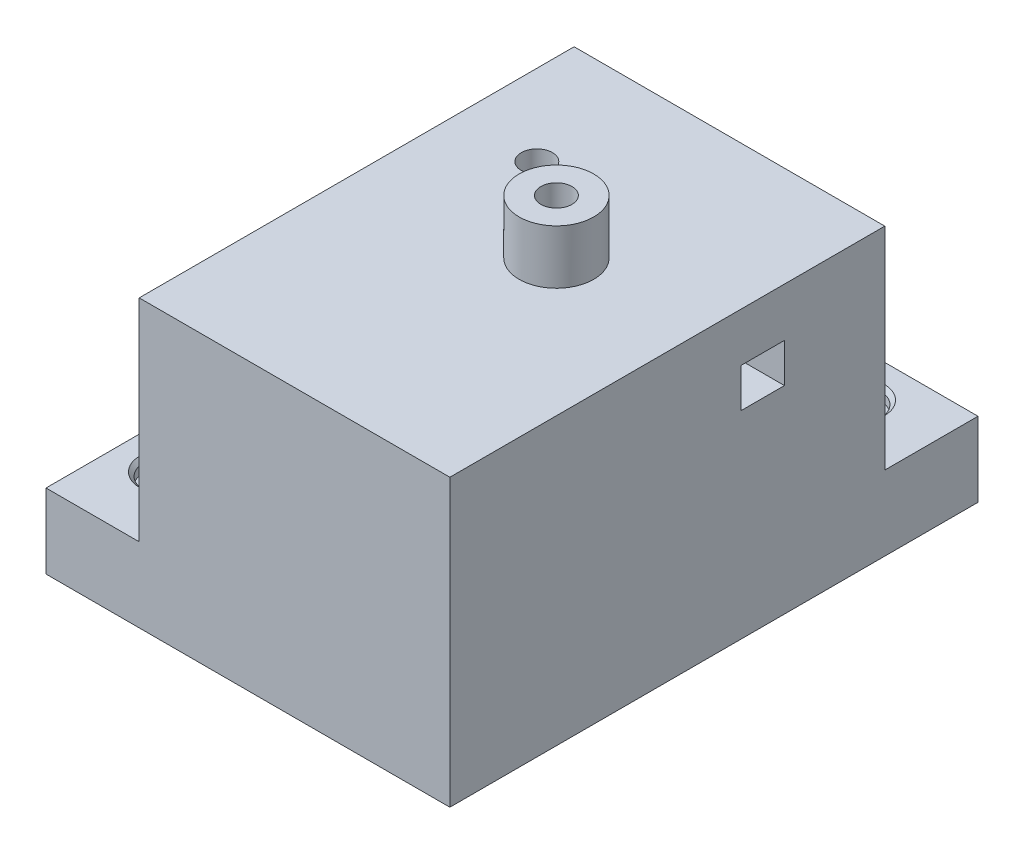
SolidWorks part; units mm, degrees
ref_plane "Front Plane" through (0, 0, 0) normal (0, 0, 1) x (1, 0, 0)
ref_plane "Top Plane" through (0, 0, 0) normal (0, 1, 0) x (1, 0, 0)
ref_plane "Right Plane" through (0, 0, 0) normal (1, 0, 0) x (0, 0, -1)
sketch "Sketch1" plane through (0, 0, 0) normal (0, 1, 0) x (1, 0, 0)
  line L1 (0, -1.9634) -> (-50, -1.9634)
  line L2 (0, -1.9634) -> (0, -71.9634)
  line L3 (0, -71.9634) -> (-50, -71.9634)
  line L4 (-50, -1.9634) -> (-50, -71.9634)
  dimension "D1" = 50
  dimension "D2" = 70
extrude "Boss-Extrude1" add sketch "Sketch1" along normal blind 46
sketch "Sketch2" plane through (0, 0, 71.9634) normal (0, 0, 1) x (1, 0, 0)
  line L0 (-50, 46) -> (0, 46) construction
  line L1 (0, 46) -> (0, 0) construction
  circle A0 centre (-25, 35) radius 3.15
  dimension "D1" = 6.3
  dimension "D2" = 11
  dimension "D3" = 25
extrude "Cut-Extrude1" cut sketch "Sketch2" against normal blind 10
sketch "Sketch3" plane through (0, 0, 0) normal (1, 0, 0) x (0, 0, -1)
  line L2 (-21.9634, 38.15) -> (-25.1134, 38.15)
  line L3 (-25.1134, 38.15) -> (-25.1134, 31.85)
  line L4 (-25.1134, 31.85) -> (-18.1134, 31.85)
  line L5 (-18.1134, 31.85) -> (-18.1134, 38.15)
  line L6 (-18.1134, 38.15) -> (-21.9634, 38.15)
  line L7 (-1.9634, 46) -> (-1.9634, 0) construction
  line L9 (-71.9634, 46) -> (-1.9634, 46) construction
  dimension "D1" = 6.3
  dimension "D2" = 16.15
  dimension "D3" = 14.15
  dimension "D4" = 7
extrude "Cut-Extrude2" cut sketch "Sketch3" against normal blind 30
sketch "Sketch4" plane through (0, 46, 0) normal (0, 1, 0) x (1, 0, 0)
  line L0 (0, -71.9634) -> (0, -1.9634) construction
  line L1 (-50, -71.9634) -> (0, -71.9634) construction
  line L2 (-50, -1.9634) -> (-50, -71.9634) construction
  circle A0 centre (-22, -32.8134) radius 2.5
  circle A1 centre (-37, -20.9634) radius 2.5
  dimension "D1" = 5
  dimension "D3" = 39.15
  dimension "D4" = 5
  dimension "D5" = 13
  dimension "D2" = 22
  dimension "D6" = 51
extrude "Cut-Extrude3" cut sketch "Sketch4" against normal blind 10
sketch "Sketch5" plane through (0, 0, 0) normal (1, 0, 0) x (0, 0, -1)
  line L0 (-1.9634, 46) -> (-1.9634, 0) construction
  line L1 (-71.9634, 0) -> (-1.9634, 0)
  line L2 (-71.9634, 0) -> (-71.9634, 12)
  line L3 (-71.9634, 12) -> (-1.9634, 12)
  line L4 (-1.9634, 0) -> (-1.9634, 12)
  dimension "D1" = 12
extrude "Boss-Extrude2" add sketch "Sketch5" along normal blind 15
sketch "Sketch6" plane through (0, 0, 1.9634) normal (0, 0, -1) x (-1, 0, 0)
  line L1 (-15, 12) -> (50, 12)
  line L2 (-15, 12) -> (-15, 0)
  line L3 (-15, 0) -> (50, 0)
  line L4 (50, 12) -> (50, 0)
extrude "Boss-Extrude3" add sketch "Sketch6" along normal blind 15
sketch "Sketch7" plane through (0, 0, 71.9634) normal (0, 0, 1) x (1, 0, 0)
  line L0 (0, 12) -> (-50, 12) construction
  line L2 (-50, 12) -> (15, 12)
  line L3 (-50, 12) -> (-50, 0)
  line L4 (-50, 0) -> (15, 0)
  line L5 (15, 12) -> (15, 0)
extrude "Boss-Extrude4" add sketch "Sketch7" along normal blind 15
sketch "Sketch8" plane through (-50, 0, 0) normal (-1, 0, 0) x (0, 0, 1)
  line L0 (-13.0366, 12) -> (86.9634, 12) construction
  line L2 (-13.0366, 0) -> (86.9634, 0)
  line L3 (-13.0366, 0) -> (-13.0366, 12)
  line L4 (-13.0366, 12) -> (86.9634, 12)
  line L5 (86.9634, 0) -> (86.9634, 12)
extrude "Boss-Extrude5" add sketch "Sketch8" along normal blind 15
sketch "Sketch9" plane through (0, 12, 0) normal (0, 1, 0) x (1, 0, 0)
  line L0 (-50, -1.9634) -> (0, -1.9634) construction
  line L1 (0, -1001.9634) -> (0, -1.9634) construction
  line L2 (15, 13.0366) -> (20.974, 13.0366) construction
  line L3 (15, 13.0366) -> (15, 18.755) construction
  line L4 (-1000, -1.9634) -> (0, -1.9634) construction
  line L5 (-65, -86.9634) -> (-65, 13.0366) construction
  line L6 (15, 13.0366) -> (-65, 13.0366)
  line L7 (15, 13.0366) -> (15, -1.9634)
  line L8 (0, -1.9634) -> (-65, -1.9634)
  line L9 (-65, 13.0366) -> (-65, -1.9634)
  line L10 (15, -1.9634) -> (25.4543, -1.9634) construction
  line L11 (15, -86.9634) -> (0, -86.9634)
  line L12 (15, -86.9634) -> (15, -1.9634)
  line L14 (0, -86.9634) -> (0, -1.9634)
extrude "Cut-Extrude4" cut sketch "Sketch9" against normal blind 15
sketch "Sketch10" plane through (0, 0, 1.9634) normal (0, 0, -1) x (-1, 0, 0)
  line L1 (0, 0) -> (65, 0)
  line L2 (0, 0) -> (0, 12)
  line L3 (0, 12) -> (65, 12)
  line L4 (65, 0) -> (65, 12)
extrude "Boss-Extrude6" add sketch "Sketch10" along normal blind 15
sketch "Sketch11" plane through (0, 12, 0) normal (0, 1, 0) x (1, 0, 0)
  line L0 (-50, -71.9634) -> (-65, -71.9634) construction
  line L1 (-65, -86.9634) -> (-65, 13.0366) construction
  line L3 (-65, -71.9634) -> (0, -71.9634)
  line L4 (-65, -71.9634) -> (-65, -86.9634)
  line L5 (-65, -86.9634) -> (0, -86.9634)
  line L6 (0, -71.9634) -> (0, -86.9634)
extrude "Cut-Extrude5" cut sketch "Sketch11" against normal blind 15
sketch "Sketch12" plane through (0, 12, 0) normal (0, 1, 0) x (1, 0, 0)
  line L0 (-50, -1.9634) -> (-65, 13.0366) construction
  line L1 (0, 13.0366) -> (0, -1.9634) construction
  line L2 (-50, -71.9634) -> (-65, -71.9634) construction
  circle A0 centre (-57.5, 5.5366) radius 3.0139
  circle A1 centre (-12, 5.5366) radius 2.6205
  circle A2 centre (-57.5, -59.9634) radius 3.0322
  dimension "D1" = 12
  dimension "D2" = 12
hole_wizard "CBORE for #5 Binding Head Machine Screw1" positions "Sketch13" profile "Sketch14" counterbore size "#5" standard "ANSI Inch" end condition through all
sketch "Sketch13" plane through (0, 12, 0) normal (0, 1, 0) x (1, 0, 0)
  point P0 (-12, 5.5366)
  point P3 (-57.5, 5.5366)
  point P6 (-57.5, -59.9634)
sketch "Sketch14" plane through (-12, 12, -5.5366) normal (1, 0, 0) x (0, 0, 1)
  line L0 (0, 0) -> (0, 12)
  line L1 (0, 12) -> (1.7272, 12)
  line L3 (1.7272, 12) -> (1.7272, 1.9812)
  line L4 (3.7706, 1.9812) -> (1.7272, 1.9812)
  line L5 (3.7706, 1.9812) -> (3.7706, 0.635)
  line L6 (3.7706, 0.635) -> (4.4056, 0)
  line L7 (4.4056, 0) -> (0, 0)
  line L8 (-3.7706, 0.635) -> (-4.4056, 0) construction
  line L11 (0, -6.35) -> (0, 107.95) construction
  dimension "Thru Hole Dia." = 3.4544
  dimension "Thru Hole Depth" = 12
  dimension "C'Bore Dia." = 7.5413
  dimension "C'Bore Depth" = 1.9812
  dimension "Near C'Sink Dia." = 8.8113
  dimension "Near C'Sink Angle" = 90
sketch "Sketch15" plane through (0, 0, 71.9634) normal (0, 0, 1) x (1, 0, 0)
  circle A0 centre (-25, 35) radius 3.15
extrude "Boss-Extrude7" add sketch "Sketch15" against normal blind 10
sketch "Sketch16" plane through (0, 46, 0) normal (0, 1, 0) x (1, 0, 0)
  circle A0 centre (-22, -32.8134) radius 2.5
  circle A1 centre (-22, -32.8134) radius 6
  dimension "D1" = 12
extrude "Boss-Extrude8" add sketch "Sketch16" along normal blind 8.7
sketch "Sketch17" plane through (-50, 0, 0) normal (-1, 0, 0) x (0, 0, 1)
  text T0 "29"
extrude "Cut-Extrude6" cut sketch "Sketch17" against normal blind 2
